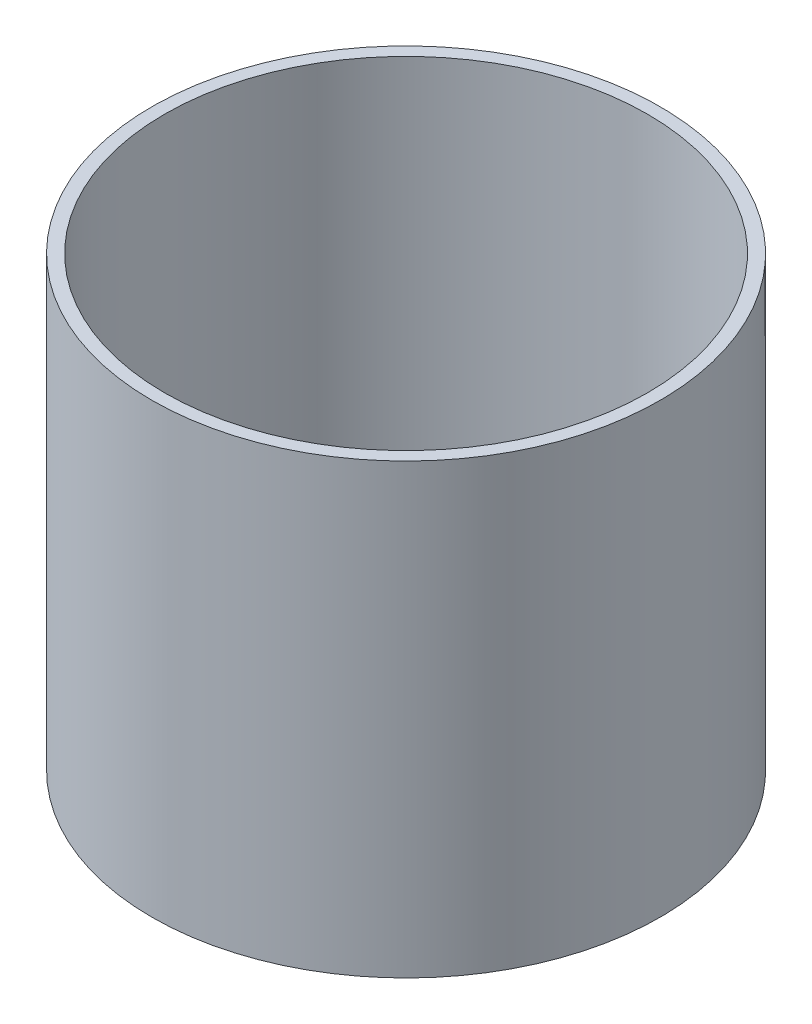
SolidWorks part; units mm, degrees
material "7075-T6 (SN)"
ref_plane "Front Plane" through (0, 0, 0) normal (0, 0, 1) x (1, 0, 0)
ref_plane "Top Plane" through (0, 0, 0) normal (0, 1, 0) x (1, 0, 0)
ref_plane "Right Plane" through (0, 0, 0) normal (1, 0, 0) x (0, 0, -1)
sketch "Sketch1" plane through (0, 0, 0) normal (0, 1, 0) x (1, 0, 0)
  circle A0 centre (0, 0) radius 37.75
  circle A1 centre (0, 0) radius 39.75
  dimension "D1" = 75.5
  dimension "D2" = 2
extrude "Boss-Extrude1" add sketch "Sketch1" along normal blind 70
